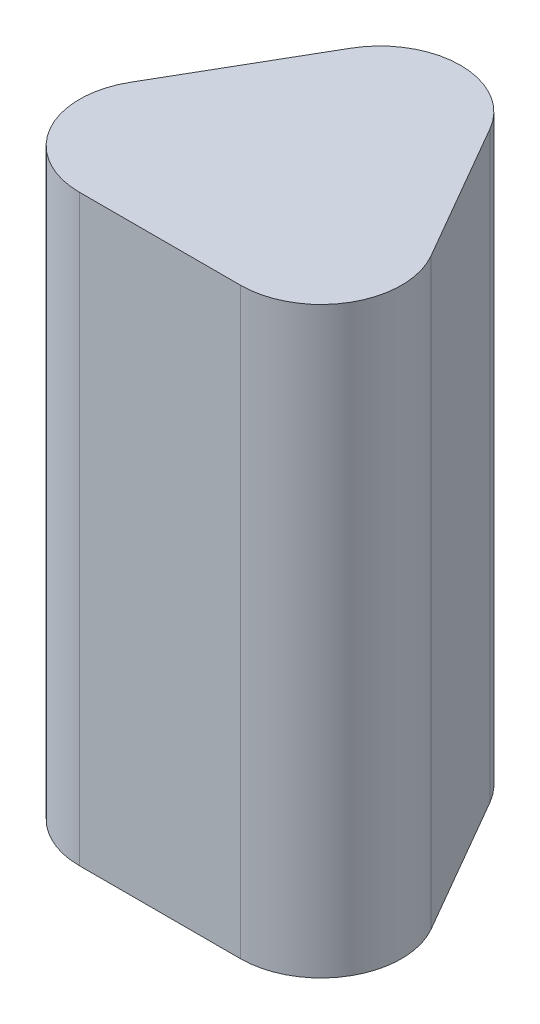
SolidWorks part; units mm, degrees
ref_plane "Front Plane" through (0, 0, 0) normal (0, 0, 1) x (1, 0, 0)
ref_plane "Top Plane" through (0, 0, 0) normal (0, 1, 0) x (1, 0, 0)
ref_plane "Right Plane" through (0, 0, 0) normal (1, 0, 0) x (0, 0, -1)
sketch "Sketch3" plane through (0, 0, 0) normal (0, 1, 0) x (1, 0, 0)
  line L0 (0, 0) -> (0, -37) construction
  line L3 (-18.5, -25.2715) -> (18.5, -25.2715) construction
  line L5 (-9.25, -34.5215) -> (9.25, -34.5215)
  line L6 (-17.2607, -20.6465) -> (-8.0107, -4.625)
  line L7 (8.0107, -4.625) -> (17.2607, -20.6465)
  arc A0 (8.0107, -4.625) -> (-8.0107, -4.625) centre (0, -9.25) ccw
  arc A1 (-17.2607, -20.6465) -> (-9.25, -34.5215) centre (-9.25, -25.2715) ccw
  arc A2 (17.2607, -20.6465) -> (9.25, -34.5215) centre (9.25, -25.2715) cw
  arc A3 (-4.625, -17.2607) -> (-17.2607, -20.6465) centre (-9.25, -25.2715) ccw construction
  arc A4 (0, -25.2715) -> (-4.625, -17.2607) centre (-9.25, -25.2715) ccw construction
  arc A5 (-4.625, -17.2607) -> (0, -18.5) centre (0, -9.25) ccw construction
  arc A6 (0, -25.2715) -> (4.625, -17.2607) centre (9.25, -25.2715) cw construction
  arc A7 (0, -18.5) -> (4.625, -17.2607) centre (0, -9.25) ccw construction
  arc A8 (4.625, -17.2607) -> (17.2607, -20.6465) centre (9.25, -25.2715) cw construction
  arc A9 (4.625, -17.2607) -> (8.0107, -4.625) centre (0, -9.25) ccw construction
  arc A10 (9.25, -34.5215) -> (0, -25.2715) centre (9.25, -25.2715) cw construction
  arc A11 (-9.25, -34.5215) -> (0, -25.2715) centre (-9.25, -25.2715) ccw construction
  arc A12 (-8.0107, -4.625) -> (-4.625, -17.2607) centre (0, -9.25) ccw construction
  dimension "D5" = 18.5
  dimension "D3" = 18.5
  dimension "D1" = 37
extrude "Boss-Extrude2" add sketch "Sketch3" along normal blind 67
